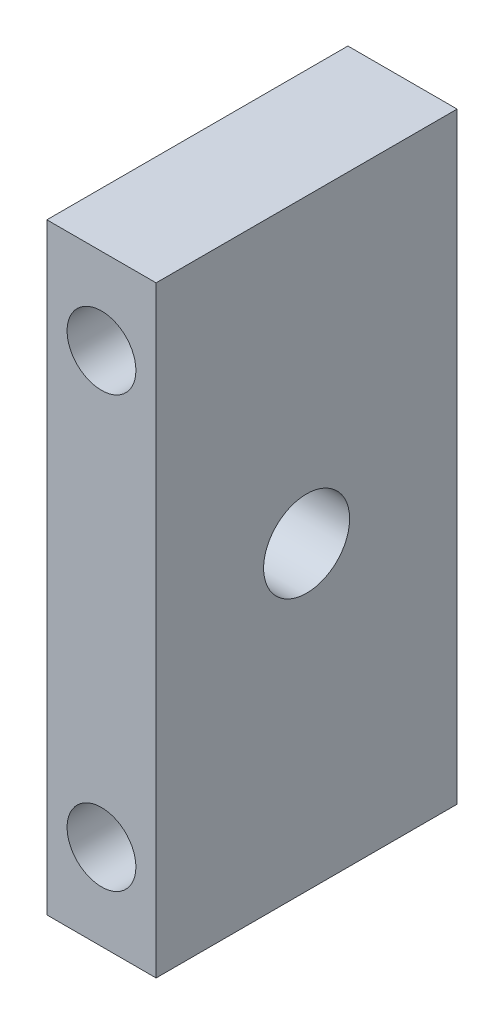
SolidWorks part; units mm, degrees
ref_plane "Alzado" through (0, 0, 0) normal (0, 0, 1) x (1, 0, 0)
ref_plane "Planta" through (0, 0, 0) normal (0, 1, 0) x (1, 0, 0)
ref_plane "Vista lateral" through (0, 0, 0) normal (1, 0, 0) x (0, 0, -1)
sketch "Croquis1" plane through (0, 0, 0) normal (1, 0, 0) x (0, 0, -1)
  line L1 (-17.5, -35) -> (17.5, -35)
  line L2 (-17.5, -35) -> (-17.5, 35)
  line L3 (-17.5, 35) -> (17.5, 35)
  line L4 (17.5, -35) -> (17.5, 35)
  line L5 (-17.5, -35) -> (17.5, 35) construction
  line L6 (-17.5, 35) -> (17.5, -35) construction
  circle A0 centre (0, 0) radius 5
  point P0 (0, 0)
  point P8 (0, 0)
  dimension "D3" = 10
  dimension "D1" = 70
  dimension "D2" = 35
extrude "Saliente-Extruir1" add sketch "Croquis1" along normal mid plane 12.7
hole_wizard "Diámetro de taladro Ø5.0 (5)1" positions "Croquis2" profile "Croquis3" hole size "Ø5.0" standard "Ansi Metric" end condition up to next
sketch "Croquis2" plane through (0, 0, 17.5) normal (0, 0, 1) x (1, 0, 0)
  line L0 (0, 25) -> (0, -25) construction
  point P0 (0, 25)
  point P2 (0, -25)
  point P10 (0, 0)
  dimension "D1" = 50
sketch "Croquis3" plane through (0, 25, 17.5) normal (1, 0, 0) x (0, -1, 0)
  line L0 (0, 0) -> (0, 35)
  line L1 (0, 35) -> (4, 35)
  line L2 (4, 35) -> (4, 0)
  line L5 (4, 0) -> (0, 0)
  line L11 (0, -6.35) -> (0, 107.95) construction
  dimension "Diámetro de taladro hasta el siguiente" = 8
  dimension "Profundidad de taladro hasta el siguiente" = 35
